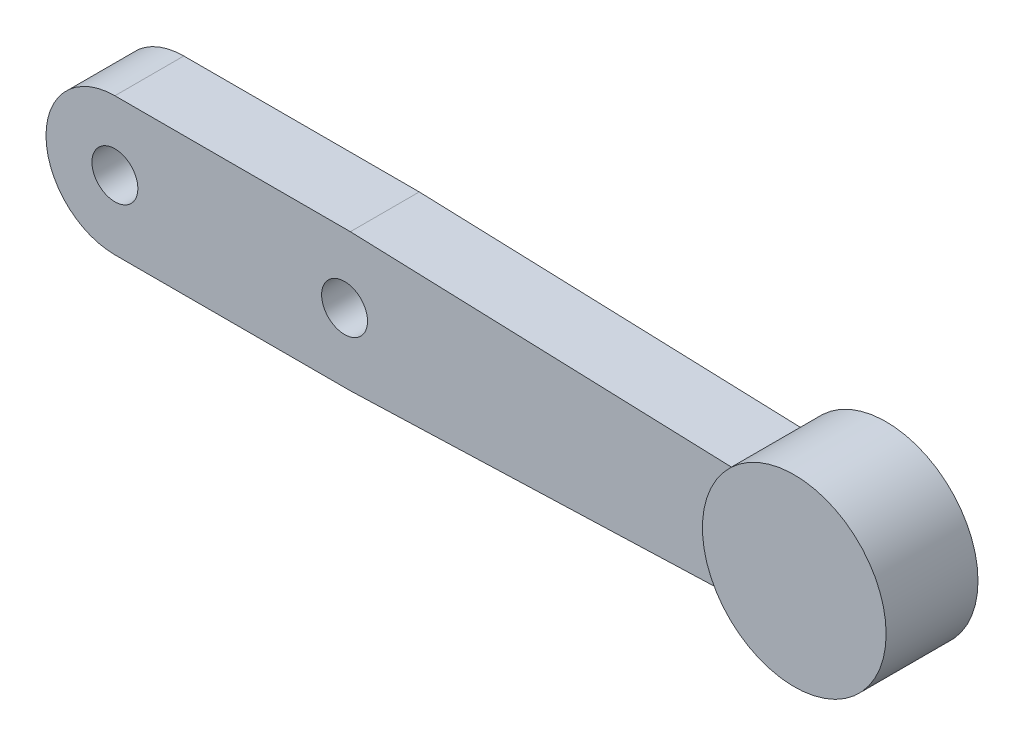
SolidWorks part; units mm, degrees
ref_plane "Front Plane" through (0, 0, 0) normal (0, 0, 1) x (1, 0, 0)
ref_plane "Top Plane" through (0, 0, 0) normal (0, 1, 0) x (1, 0, 0)
ref_plane "Right Plane" through (0, 0, 0) normal (1, 0, 0) x (0, 0, -1)
sketch "Sketch1" plane through (0, 0, 0) normal (0, 0, 1) x (1, 0, 0)
  line L0 (0.6318, 7.5059) -> (50.2015, 5.7749)
  line L1 (0.6318, -7.4941) -> (50.2015, -5.7631)
  line L2 (-1025, 0.0059) -> (48975, 0.0059) construction
  line L3 (0.6318, 7.5059) -> (-25, 7.5059)
  line L4 (0.2967, 2.4823) -> (0.2967, -2.4823)
  line L5 (0.6318, -7.4941) -> (-25, -7.4941)
  line L6 (-25, 7.5059) -> (-25, -7.4941)
  circle A0 centre (0, 0) radius 2.5
  arc A3 (50.2015, -5.7631) -> (50.2015, 5.7749) centre (50, 0.0059) ccw
  circle A4 centre (-25, 0.0059) radius 7.5
  circle A5 centre (-25, 0.0059) radius 2.5
  dimension "D1" = 5
  dimension "D2" = 15
  dimension "D4" = 25
  dimension "D3" = 50
  dimension "D5" = 182
extrude "Boss-Extrude1" add sketch "Sketch1" along normal mid plane 7.5 contours A4 L2 A5 L6 | A5 L2 A4 L6 | L2 A4 L6 A5 | L2 A5 L6 A4 | L2 A4 L5 L1 A3 A0 | A4 L2 A0 A3 L0 L3
sketch "Sketch2" plane through (0, 0, 0) normal (0, 0, 1) x (1, 0, 0)
  circle A2 centre (50.2015, 0.0059) radius 10
  dimension "D1" = 20
extrude "Boss-Extrude2" add sketch "Sketch2" along normal mid plane 10
